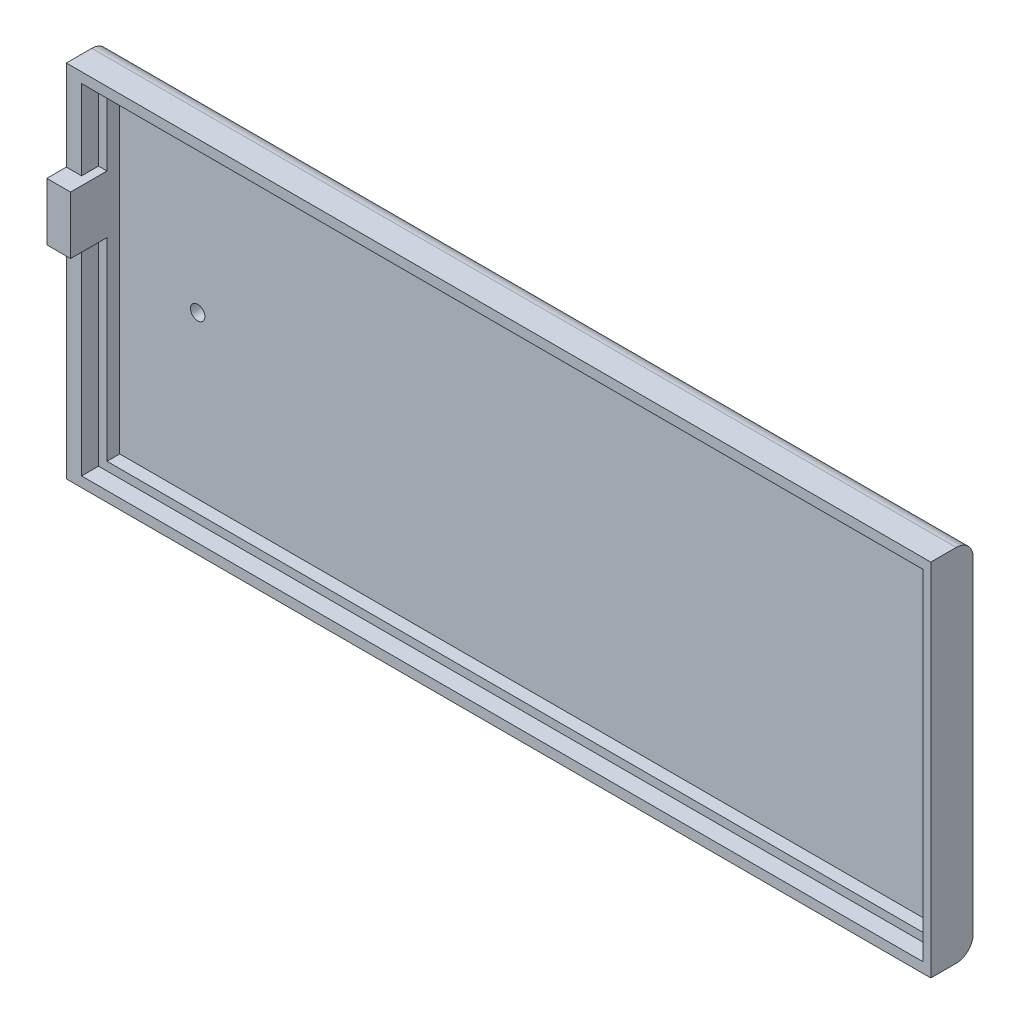
SolidWorks part; units mm, degrees
ref_plane "Front Plane" through (0, 0, 0) normal (0, 0, 1) x (1, 0, 0)
ref_plane "Top Plane" through (0, 0, 0) normal (0, 1, 0) x (1, 0, 0)
ref_plane "Right Plane" through (0, 0, 0) normal (1, 0, 0) x (0, 0, -1)
sketch "Sketch2" plane through (0, 0, 0) normal (0, 0, 1) x (1, 0, 0)
  line L1 (0, 0) -> (102, 0)
  line L2 (0, 0) -> (0, 42.5)
  line L3 (0, 42.5) -> (102, 42.5)
  line L4 (102, 0) -> (102, 42.5)
  dimension "D1" = 102
  dimension "D2" = 42.5
extrude "Boss-Extrude1" add sketch "Sketch2" along normal blind 5
sketch "Sketch3" plane through (0, 0, 5) normal (0, 0, 1) x (1, 0, 0)
  line L0 (0, 21.25) -> (102, 21.25) construction
  line L1 (0, 42.5) -> (0, 0) construction
  line L2 (102, 0) -> (102, 42.5) construction
  line L3 (102, 42.5) -> (0, 42.5) construction
  line L4 (2.8, 40.3) -> (100.1, 40.3)
  line L5 (2.8, 40.3) -> (2.8, 2.2)
  line L6 (2.8, 2.2) -> (100.1, 2.2)
  line L7 (100.1, 40.3) -> (100.1, 2.2)
  line L8 (0, 0) -> (102, 0) construction
  dimension "D1" = 2.8
  dimension "D2" = 1.9
  dimension "D3" = 2.2
  dimension "D4" = 2.2
extrude "Cut-Extrude1" cut sketch "Sketch3" against normal blind 3.5
sketch "Sketch4" plane through (0, 0, 5) normal (0, 0, 1) x (1, 0, 0)
  line L0 (0, 0) -> (0, 10.6365) construction
  line L1 (0, 42.5) -> (0, 0) construction
  line L2 (2.8, 40.3) -> (2.8, 2.2) construction
  line L3 (0, 10.6365) -> (2.8, 10.6365) construction
  line L4 (0, 10.6365) -> (0, 17.4365) construction
  line L5 (0, 17.4365) -> (2.8, 17.4365) construction
  line L6 (2.8, 10.6365) -> (2.8, 17.4365) construction
  line L7 (0, 21.25) -> (102, 21.25) construction
  line L8 (102, 0) -> (102, 42.5) construction
  line L9 (0, 25.0635) -> (2.8, 25.0635)
  line L10 (2.8, 31.8635) -> (2.8, 25.0635)
  line L11 (0, 31.8635) -> (2.8, 31.8635)
  line L12 (0, 31.8635) -> (0, 25.0635)
  dimension "D1" = 6.8
  dimension "D2" = 2.8
sketch "Sketch7" plane through (0, 0, 1.5) normal (0, 0, 1) x (1, 0, 0)
  line L0 (0, 21.25) -> (102, 21.25) construction
  line L1 (0, 42.5) -> (0, 0) construction
  line L2 (102, 0) -> (102, 42.5) construction
extrude "Boss-Extrude3" add sketch "Sketch4" along normal blind 2.3
sketch "Sketch8" plane through (0, 0, 5) normal (0, 0, 1) x (1, 0, 0)
  line L0 (2.8, 31.8635) -> (1.8, 31.8635)
  line L1 (2.8, 31.8635) -> (0, 31.8635) construction
  line L2 (1.8, 31.8635) -> (1.8, 41.3)
  line L3 (1.8, 41.3) -> (101.1, 41.3)
  line L4 (101.1, 41.3) -> (101.1, 1.2)
  line L5 (101.1, 1.2) -> (1.8, 1.2)
  line L6 (1.8, 1.2) -> (1.8, 25.0635)
  line L7 (0, 25.0635) -> (2.8, 25.0635) construction
  line L8 (1.8, 25.0635) -> (2.8, 25.0635)
  line L9 (2.8, 25.0635) -> (2.8, 2.2)
  line L10 (2.8, 2.2) -> (100.1, 2.2)
  line L11 (100.1, 2.2) -> (100.1, 40.3)
  line L12 (100.1, 40.3) -> (2.8, 40.3)
  line L13 (2.8, 40.3) -> (2.8, 31.8635)
  dimension "D1" = 1
  dimension "D2" = 1
  dimension "D3" = 1
  dimension "D4" = 1
  dimension "D5" = 1
extrude "Cut-Extrude4" cut sketch "Sketch8" against normal blind 2
sketch "Sketch9" plane through (0, 0, 1.5) normal (0, 0, 1) x (1, 0, 0)
  line L1 (0, 42.5) -> (12, 42.5) construction
  line L2 (0, 42.5) -> (0, 21.25) construction
  line L3 (0, 21.25) -> (12, 21.25) construction
  line L4 (12, 42.5) -> (12, 21.25) construction
  circle A0 centre (12, 21.25) radius 0.85
  dimension "D1" = 12
  dimension "D2" = 21.25
extrude "Cut-Extrude5" cut sketch "Sketch9" against normal blind 31
fillet "Fillet1" radius 2 2 edges at (51, 0, 0) (51, 42.5, 0)
